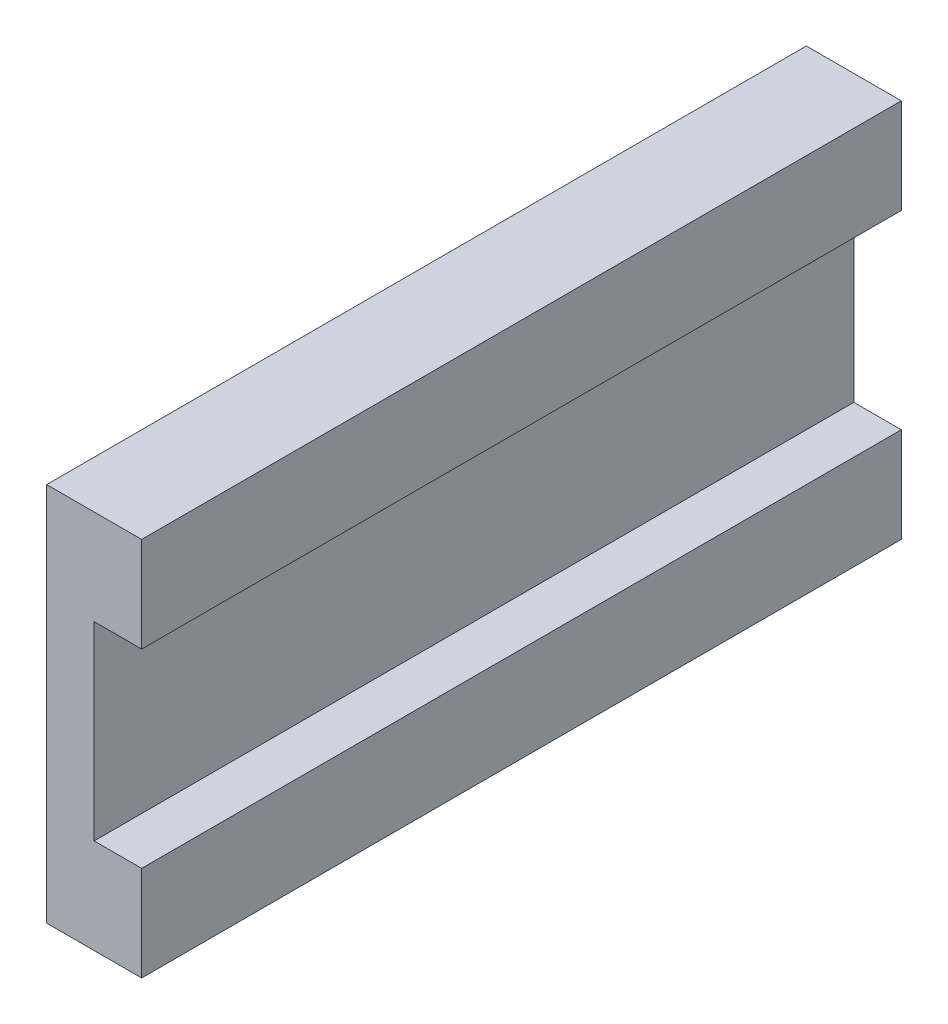
SolidWorks part; units mm, degrees
material "1.0037 (S235JR)"
ref_plane "Front Plane" through (0, 0, 0) normal (0, 0, 1) x (1, 0, 0)
ref_plane "Top Plane" through (0, 0, 0) normal (0, 1, 0) x (1, 0, 0)
ref_plane "Right Plane" through (0, 0, 0) normal (1, 0, 0) x (0, 0, -1)
sketch "Esquisse1" plane through (0, 0, 0) normal (0, 0, 1) x (1, 0, 0)
  line L0 (0, 0) -> (0, 80)
  line L1 (0, 80) -> (20, 80)
  line L2 (20, 80) -> (20, 60)
  line L3 (20, 60) -> (10, 60)
  line L4 (10, 60) -> (10, 20)
  line L5 (10, 20) -> (20, 20)
  line L6 (20, 20) -> (20, 0)
  line L7 (20, 0) -> (0, 0)
  dimension "D1" = 80
  dimension "D2" = 20
  dimension "D3" = 20
  dimension "D4" = 10
extrude "Boss.-Extru.1" add sketch "Esquisse1" along normal mid plane 160
